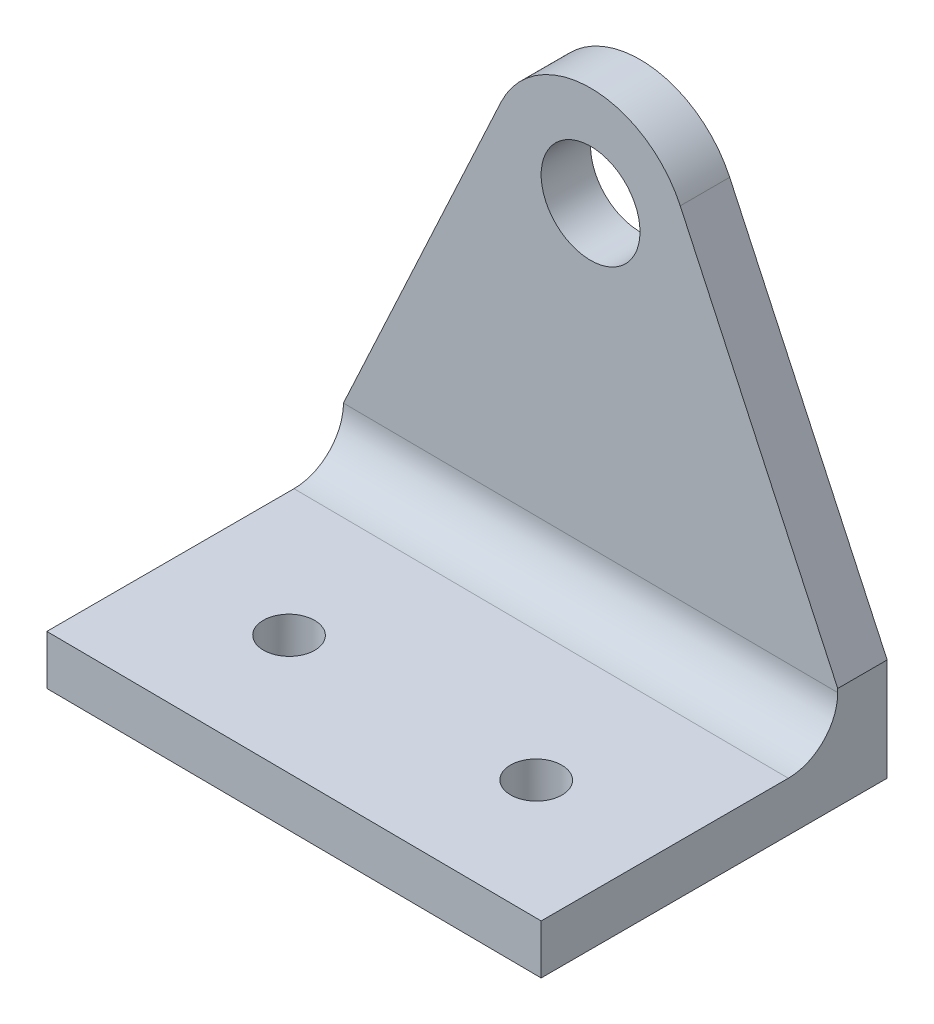
SolidWorks part; units mm, degrees
material "스테인리스 강(페라이트)"
ref_plane "Front Plane" through (0, 0, 0) normal (0, 0, 1) x (1, 0, 0)
ref_plane "Top Plane" through (0, 0, 0) normal (0, 1, 0) x (1, 0, 0)
ref_plane "Right Plane" through (0, 0, 0) normal (1, 0, 0) x (0, 0, -1)
sketch "Sketch1" plane through (0, 0, 0) normal (0, 0, 1) x (1, 0, 0)
  line L0 (0, 0) -> (0, 32.3995) construction
  line L1 (-9.0702, 4.3131) -> (-25, -30)
  line L2 (9.0702, 4.3131) -> (25, -30)
  line L3 (-25, -30) -> (-25, -40)
  line L4 (-25, -40) -> (25, -40.3636)
  line L5 (25, -40.3636) -> (25, -30)
  circle A0 centre (0, 0) radius 5
  arc A1 (-9.0702, 4.3131) -> (9.0702, 4.3131) centre (0, 0.1023) cw
  dimension "D1" = 10
  dimension "D3" = 10
  dimension "D4" = 10
  dimension "D2" = 50
  dimension "D5" = 40
extrude "Boss-Extrude1" add sketch "Sketch1" along normal blind 5
sketch "Sketch6" plane through (0, 0, 5) normal (0, 0, 1) x (1, 0, 0)
  line L0 (-25, -35) -> (-25, -40)
  line L1 (-25, -30) -> (-25, -40) construction
  line L2 (-25, -40) -> (25, -40.3636)
  line L3 (25, -40.3636) -> (25, -35.3636)
  line L4 (25, -40.3636) -> (25, -30) construction
  line L5 (-25, -35) -> (25, -35.3636)
  dimension "D1" = 5
extrude "Boss-Extrude2" add sketch "Sketch6" along normal blind 30 contours L5 L3 L2 L0
fillet "Fillet1" radius 5 1 edges at (0, -35.1818, 5)
sketch "Sketch7" plane through (-0.2558, -35.1799, 0) normal (0.0073, 1, 0) x (1, -0.0073, 0)
  line L0 (0, 0) -> (0, -35) construction
  line L1 (-24.7448, -35) -> (25.2565, -35) construction
  line L2 (-24.7448, -35) -> (-24.7448, -10) construction
  circle A0 centre (-12.2448, -23) radius 2.6
  dimension "D1" = 12.5
  dimension "D2" = 12
extrude "Cut-Extrude1" cut sketch "Sketch7" against normal blind 30
mirror "Mirror2" about plane through (0, 0, 0) normal (1, 0, 0) of "Cut-Extrude1"
